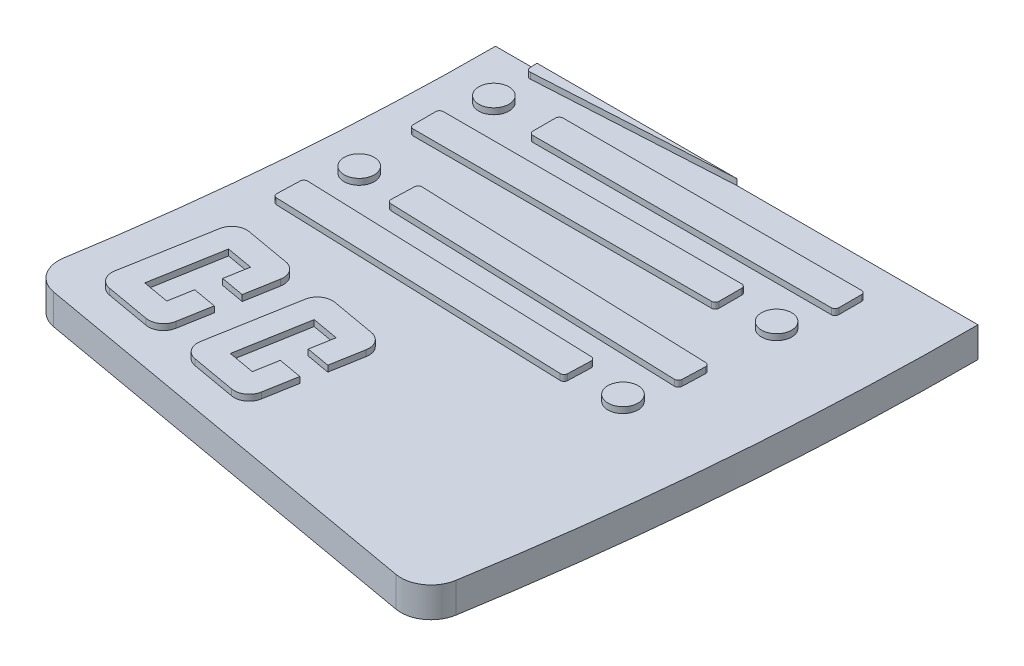
SolidWorks part; units mm, degrees
material "6061-T4 (SS)"
ref_plane "Front" through (0, 0, 0) normal (0, 0, 1) x (1, 0, 0)
ref_plane "Top" through (0, 0, 0) normal (0, 1, 0) x (1, 0, 0)
ref_plane "Right" through (0, 0, 0) normal (1, 0, 0) x (0, 0, -1)
sketch "Sketch1" plane through (0, 0, 0) normal (0, 1, 0) x (1, 0, 0)
  line L0 (-101.6, 0) -> (101.6, 0)
  line L1 (-117.4153, -180.5061) -> (82.6886, -215.8422)
  line L2 (-101.6, 0) -> (-101.6, 83.31) construction
  arc A0 (-101.6, 0) -> (-117.4153, -180.5061) centre (-1139.598, 0) cw
  arc A1 (82.6886, -215.8422) -> (101.6, 0) centre (-1139.598, 0) ccw
  point P2 (81.5997, -228.6044)
  point P6 (156.6066, -240.5489)
  point P7 (-6.7004, -76.586)
  point P8 (182.0957, -241.2242)
  point P9 (0, 0)
  point P11 (38.3205, -25.2198)
  point P13 (88.6269, -184.963)
  point P14 (82.6886, -215.8422)
  dimension "D1" = 203.2
extrude "Boss-Extrude1" add sketch "Sketch1" along normal blind 12.7
fillet "Fillet1" radius 12.7 2 edges at (82.6886, 6.35, 215.8422) (-117.4153, 6.35, 180.5061)
sketch "Sketch2" plane through (0, 12.7, 0) normal (0, 1, 0) x (1, 0, 0)
  line L12 (-54.6146, -178.6995) -> (-23.3484, -184.2208)
  line L13 (-84.9628, -186.2369) -> (-82.7543, -173.7304) construction
  line L14 (-104.9844, -182.7012) -> (70.1175, -213.6223) construction
  line L15 (-98.3874, -170.9697) -> (-67.1211, -176.491)
  line L16 (-98.3874, -170.9697) -> (-89.5533, -120.9437)
  line L17 (-89.5533, -120.9437) -> (-58.2871, -126.465)
  line L18 (-58.2871, -126.465) -> (-61.8207, -146.4754)
  line L19 (-61.8207, -146.4754) -> (-71.8259, -144.7086)
  line L20 (-71.8259, -144.7086) -> (-70.0591, -134.7034)
  line L21 (-70.0591, -134.7034) -> (-81.315, -132.7157)
  line L22 (-81.315, -132.7157) -> (-86.6154, -162.7313)
  line L23 (-86.6154, -162.7313) -> (-75.3595, -164.719)
  line L24 (-75.3595, -164.719) -> (-73.5927, -154.7138)
  line L25 (-73.5927, -154.7138) -> (-63.5875, -156.4806)
  line L26 (-63.5875, -156.4806) -> (-67.1211, -176.491)
  line L27 (-82.7543, -173.7304) -> (-80.9874, -163.7252) construction
  line L28 (-83.9652, -147.7235) -> (-93.9704, -145.9567) construction
  line L29 (-54.6146, -178.6995) -> (-45.7806, -128.6735)
  line L30 (-45.7806, -128.6735) -> (-14.5144, -134.1948)
  line L31 (-14.5144, -134.1948) -> (-18.048, -154.2052)
  line L32 (-18.048, -154.2052) -> (-28.0532, -152.4384)
  line L33 (-28.0532, -152.4384) -> (-26.2864, -142.4332)
  line L34 (-26.2864, -142.4332) -> (-37.5422, -140.4455)
  line L35 (-37.5422, -140.4455) -> (-42.8426, -170.4611)
  line L36 (-42.8426, -170.4611) -> (-31.5868, -172.4488)
  line L37 (-31.5868, -172.4488) -> (-29.82, -162.4436)
  line L38 (-29.82, -162.4436) -> (-19.8148, -164.2104)
  line L39 (-19.8148, -164.2104) -> (-23.3484, -184.2208)
  line L40 (-38.9815, -181.4601) -> (-37.2147, -171.4549) construction
  line L41 (-40.1924, -155.4533) -> (-50.1976, -153.6865) construction
  point P7 (-82.7543, -173.7304)
  point P19 (-83.865, -154.1005)
  point P21 (-71.3484, -151.5036)
  point P22 (-92.7678, -135.0857)
  point P23 (-49.0934, -117.5608)
  point P24 (-57.3767, -124.5561)
  point P25 (-82.9, -175.7852)
  point P26 (-81.9895, -119.6101)
  point P27 (-80.9874, -119.6571)
  point P33 (-38.9815, -181.4601)
  point P46 (0, 0)
  point P47 (0, 0)
  point P48 (-7.2779, -147.9854)
  dimension "D1" = 10.16
  dimension "D2" = 10.16
  dimension "D3" = 12.7
  dimension "D4" = 50.8
  dimension "D5" = 31.75
  dimension "D6" = 33.0309
  dimension "D7" = 10.16
  dimension "D8" = 12.7
extrude "Boss-Extrude2" add sketch "Sketch2" along normal blind 2.54
fillet "Fillet2" radius 6.35 8 edges at (-54.6146, 13.97, 178.6995) (-23.3484, 13.97, 184.2208) (-14.5144, 13.97, 134.1948) (-45.7806, 13.97, 128.6735) (-67.1211, 13.97, 176.491) (-98.3874, 13.97, 170.9697) (-89.5533, 13.97, 120.9437) (-58.2871, 13.97, 126.465)
sketch "Sketch3" plane through (0, 12.7, 0) normal (0, 1, 0) x (1, 0, 0)
  line L0 (-84.0615, -74.9557) -> (-1.5618, -77.8367) construction
  line L1 (-65.2447, -81.9667) -> (61.6779, -86.3989)
  line L2 (-65.2447, -81.9667) -> (-64.8015, -69.2744)
  line L3 (61.6779, -86.3989) -> (62.1212, -73.7067)
  line L4 (-64.8015, -69.2744) -> (62.1212, -73.7067)
  line L5 (-65.2447, -81.9667) -> (62.1212, -73.7067) construction
  line L6 (61.6779, -86.3989) -> (-64.8015, -69.2744) construction
  line L7 (101.6, 0) -> (-101.6, 0) construction
  line L8 (-91.427, -103.9263) -> (35.4956, -108.3586)
  line L9 (-91.427, -103.9263) -> (-90.9838, -91.2341)
  line L10 (35.4956, -108.3586) -> (35.9388, -95.6663)
  line L11 (-90.9838, -91.2341) -> (35.9388, -95.6663)
  line L12 (-91.427, -103.9263) -> (35.9388, -95.6663) construction
  line L13 (35.4956, -108.3586) -> (-90.9838, -91.2341) construction
  line L14 (54.7556, -102.6773) -> (35.7172, -102.0124) construction
  line L15 (-81.4434, -20.8685) -> (4.1802, -20.8685) construction
  line L16 (-60.2412, -27.2185) -> (68.6015, -27.2185)
  line L17 (-60.2412, -27.2185) -> (-60.2412, -14.5185)
  line L18 (68.6015, -27.2185) -> (68.6015, -14.5185)
  line L19 (-60.2412, -14.5185) -> (68.6015, -14.5185)
  line L20 (-60.2412, -27.2185) -> (68.6015, -14.5185) construction
  line L21 (68.6015, -27.2185) -> (-60.2412, -14.5185) construction
  line L22 (-87.7934, -50.0785) -> (41.0493, -50.0785)
  line L23 (-87.7934, -50.0785) -> (-87.7934, -37.3785)
  line L24 (41.0493, -50.0785) -> (41.0493, -37.3785)
  line L25 (-87.7934, -37.3785) -> (41.0493, -37.3785)
  line L26 (-87.7934, -50.0785) -> (41.0493, -37.3785) construction
  line L27 (41.0493, -50.0785) -> (-87.7934, -37.3785) construction
  line L28 (60.4958, -43.7285) -> (41.0493, -43.7285) construction
  line L29 (-84.1538, 0) -> (-83.8826, -4.7697)
  line L30 (-83.8826, -4.7697) -> (0, 0)
  line L31 (-84.1538, 0) -> (0, 0)
  circle A0 centre (-84.0615, -74.9557) radius 6.35
  circle A1 centre (54.7556, -102.6773) radius 6.35
  circle A2 centre (-81.4434, -20.8685) radius 6.35
  circle A3 centre (60.4958, -43.7285) radius 6.35
  point P2 (-83.8826, 0)
  point P15 (-27.7441, -99.7963)
  point P29 (-23.3721, -43.7285)
  dimension "D1" = 127
  dimension "D2" = 12.7
  dimension "D3" = 19.05
  dimension "D4" = 2
  dimension "D5" = 19.05
  dimension "D6" = 10.16
  dimension "D7" = 12.7
  dimension "D8" = 10.16
extrude "Boss-Extrude3" add sketch "Sketch3" along normal blind 2.54
fillet "Fillet3" radius 1.5875 17 edges at (-65.2447, 13.97, 81.9667) (61.6779, 13.97, 86.3989) (-64.8015, 13.97, 69.2744) (62.1212, 13.97, 73.7067) (-91.427, 13.97, 103.9263) (35.4956, 13.97, 108.3586) (-90.9838, 13.97, 91.2341) (35.9388, 13.97, 95.6663) (-83.8826, 13.97, 4.7697) (68.6015, 13.97, 27.2185) (68.6015, 13.97, 14.5185) (-60.2412, 13.97, 14.5185) (-60.2412, 13.97, 27.2185) (-87.7934, 13.97, 50.0785) (41.0493, 13.97, 50.0785) (41.0493, 13.97, 37.3785) (-87.7934, 13.97, 37.3785)
equation "\"D5@Sketch3\"=\"D3@Sketch3\""
